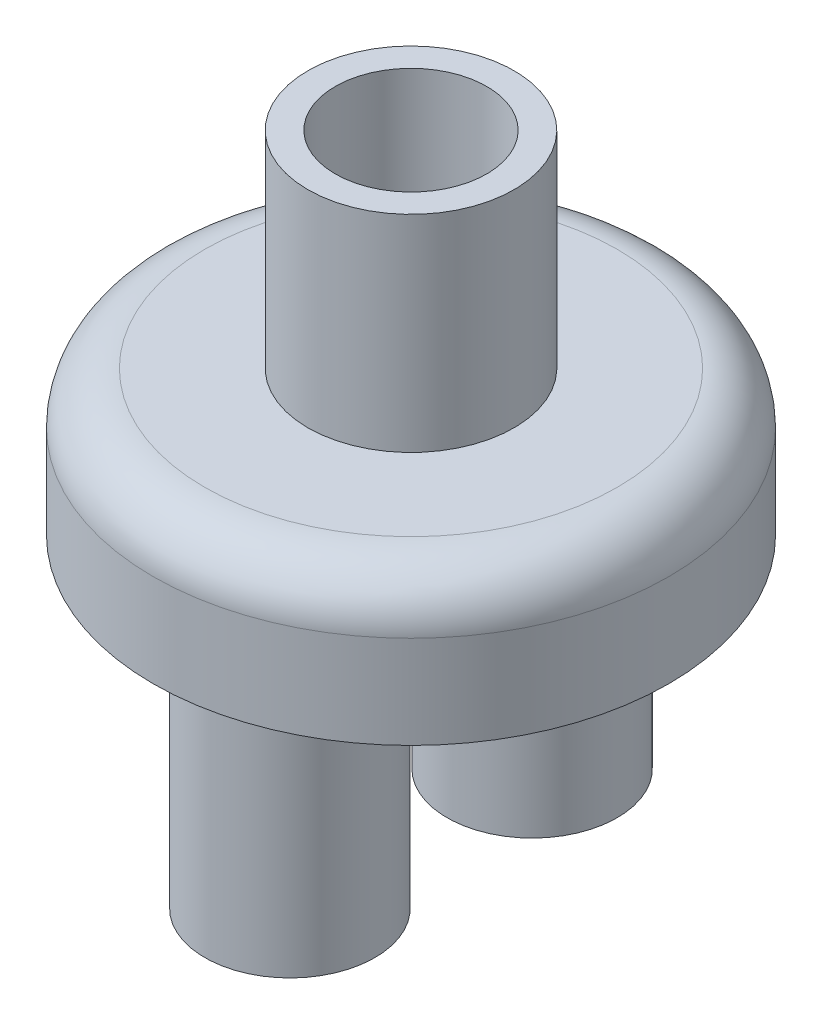
SolidWorks part; units mm, degrees
material "6061 Alloy"
ref_plane "Front Plane" through (0, 0, 0) normal (0, 0, 1) x (1, 0, 0)
ref_plane "Top Plane" through (0, 0, 0) normal (0, 1, 0) x (1, 0, 0)
ref_plane "Right Plane" through (0, 0, 0) normal (1, 0, 0) x (0, 0, -1)
sketch "Sketch1" plane through (0, 0, 0) normal (0, 1, 0) x (1, 0, 0)
  circle A0 centre (0, 0) radius 10
extrude "Boss-Extrude1" add sketch "Sketch1" along normal blind 20
sketch "Sketch2" plane through (0, 0, 0) normal (0, -1, 0) x (1, 0, 0)
  circle A0 centre (0, 0) radius 25
extrude "Boss-Extrude2" add sketch "Sketch2" along normal blind 22
sketch "Sketch3" plane through (0, -22, 0) normal (0, -1, 0) x (1, 0, 0)
  circle A0 centre (0, 0) radius 20.5
extrude "Cut-Extrude1" cut sketch "Sketch3" against normal blind 20
fillet "Fillet1" radius 5 1 edges at (0, 0, -25)
sketch "Sketch4" plane through (0, 20, 0) normal (0, 1, 0) x (1, 0, 0)
  circle A0 centre (0, 0) radius 7.35
extrude "Cut-Extrude2" cut sketch "Sketch4" against normal blind 20
sketch "Sketch5" plane through (0, -2, 0) normal (0, -1, 0) x (1, 0, 0)
  line L0 (0, -11.7483) -> (0, 11.7483) construction
  circle A0 centre (0, 11.7483) radius 8.25
  circle A1 centre (0, -11.7483) radius 8.25
  point P6 (0, 0)
  dimension "D1" = 16.5
extrude "Boss-Extrude3" add sketch "Sketch5" along normal blind 37.5
sketch "Sketch6" plane through (0, -39.5, 0) normal (0, -1, 0) x (1, 0, 0)
  circle A0 centre (0, 11.7483) radius 4.5
  circle A1 centre (0, -11.7483) radius 4.5
  dimension "D1" = 9
  dimension "D2" = 9
extrude "Cut-Extrude3" cut sketch "Sketch6" against normal blind 30
sketch "Sketch7" plane through (0, -22, 0) normal (0, -1, 0) x (1, 0, 0)
  circle A2 centre (0, 0) radius 25
  circle A3 centre (0, 0) radius 25
  circle A5 centre (0, 0) radius 20.5
  circle A6 centre (0, 0) radius 20.5
  dimension "D1" = 0
  dimension "D2" = 0
extrude "Cut-Extrude4" cut sketch "Sketch7" against normal blind 8
